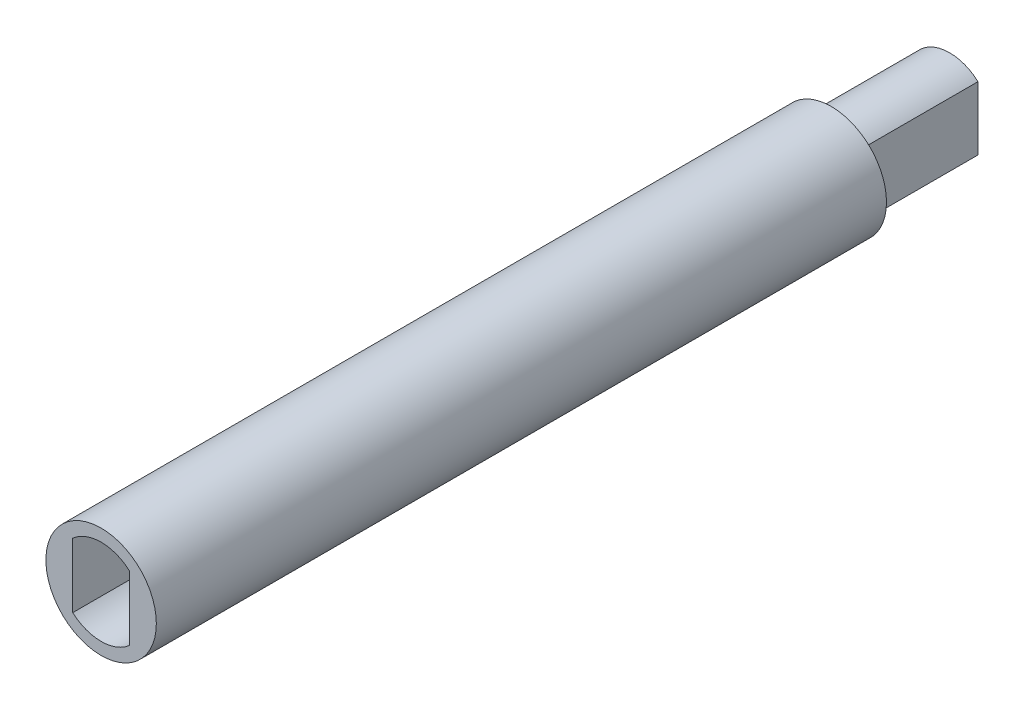
SolidWorks part; units mm, degrees
ref_plane "Alzado" through (0, 0, 0) normal (0, 0, 1) x (1, 0, 0)
ref_plane "Planta" through (0, 0, 0) normal (0, 1, 0) x (1, 0, 0)
ref_plane "Vista lateral" through (0, 0, 0) normal (1, 0, 0) x (0, 0, -1)
sketch "Croquis1" plane through (0, 0, 0) normal (0, 0, 1) x (1, 0, 0)
  circle A0 centre (0, 0) radius 3.5
  dimension "D1" = 7
extrude "Saliente-Extruir1" add sketch "Croquis1" against normal blind 65.5
sketch "Croquis6" plane through (0, 0, 0) normal (0, 0, 1) x (1, 0, 0)
  line L0 (0, 0) -> (-1.8, 0) construction
  line L1 (-1.8, 0) -> (0, 0) construction
  line L2 (0, 0) -> (0, 0.6701) construction
  line L3 (-1.8, 2.0459) -> (-1.8, -2.0459)
  line L4 (1.8, 2.0459) -> (1.8, -2.0459)
  arc A1 (-1.8, -2.0459) -> (1.8, -2.0459) centre (0, 0) ccw
  arc A2 (1.8, 2.0459) -> (-1.8, 2.0459) centre (0, 0) ccw
  point P9 (-1.8, 0)
  dimension "D2" = 5.45
  dimension "D1" = 1.8
  dimension "D3" = 1.8
extrude "Cortar-Extruir3" cut sketch "Croquis6" against normal blind 8
sketch "Croquis7" plane through (0, 0, -65.5) normal (0, 0, -1) x (-1, 0, 0)
  line L0 (0, 0.6984) -> (0, 0) construction
  line L1 (0, 0) -> (-1.8, 0) construction
  line L2 (-1.8, 2.0125) -> (-1.8, -2.0125)
  line L3 (1.8, 2.0125) -> (1.8, -2.0125)
  arc A0 (-1.8, -2.0125) -> (1.8, -2.0125) centre (0, 0) ccw
  arc A1 (1.8, 2.0125) -> (-1.8, 2.0125) centre (0, 0) ccw
  point P8 (-1.8, 0)
  circle M7 centre (0, 0) radius 3.5
  dimension "D1" = 5.4
  dimension "D2" = 1.8
extrude "Cortar-Extruir5" cut sketch "Croquis7" against normal blind 20 contours A1 L3 A0 L2 M7
sketch "Croquis8" plane through (-1.8, 0, 0) normal (-1, 0, 0) x (0, 0, 1)
  line L0 (-45.5, -0.4367) -> (-53, -0.4367) construction
  line L1 (-45.5, 2.0125) -> (-45.5, -2.0125) construction
  line L2 (-53, 4.2047) -> (-53, -5.0782)
  line L3 (-53, -5.0782) -> (-65.6172, -5.0782)
  line L4 (-65.6172, 4.2047) -> (-53, 4.2047)
  line L5 (-65.6172, 4.2047) -> (-65.6172, -5.0782)
  point P7 (-53, -0.4367)
  dimension "D1" = 7.5
extrude "Cortar-Extruir6" cut sketch "Croquis8" against normal blind 10
sketch "Croquis10" plane through (0, 0, 0) normal (0, 0, 1) x (1, 0, 0)
  line L0 (-1.8, 2.0459) -> (-1.8, -2.0459)
  line L1 (1.8, 2.0459) -> (1.8, -2.0459)
  circle A0 centre (0, 0) radius 3.5
  arc A1 (-1.8, -2.0459) -> (1.8, -2.0459) centre (0, 0) ccw
  arc A2 (1.8, 2.0459) -> (-1.8, 2.0459) centre (0, 0) ccw
extrude "Saliente-Extruir2" add sketch "Croquis10" along normal blind 2.5
sketch "Croquis11" plane through (0, 0, 2.5) normal (0, 0, 1) x (1, 0, 0)
  circle A0 centre (0, 0) radius 3.5
extrude "Cortar-Extruir7" cut sketch "Croquis11" against normal blind 1.72
